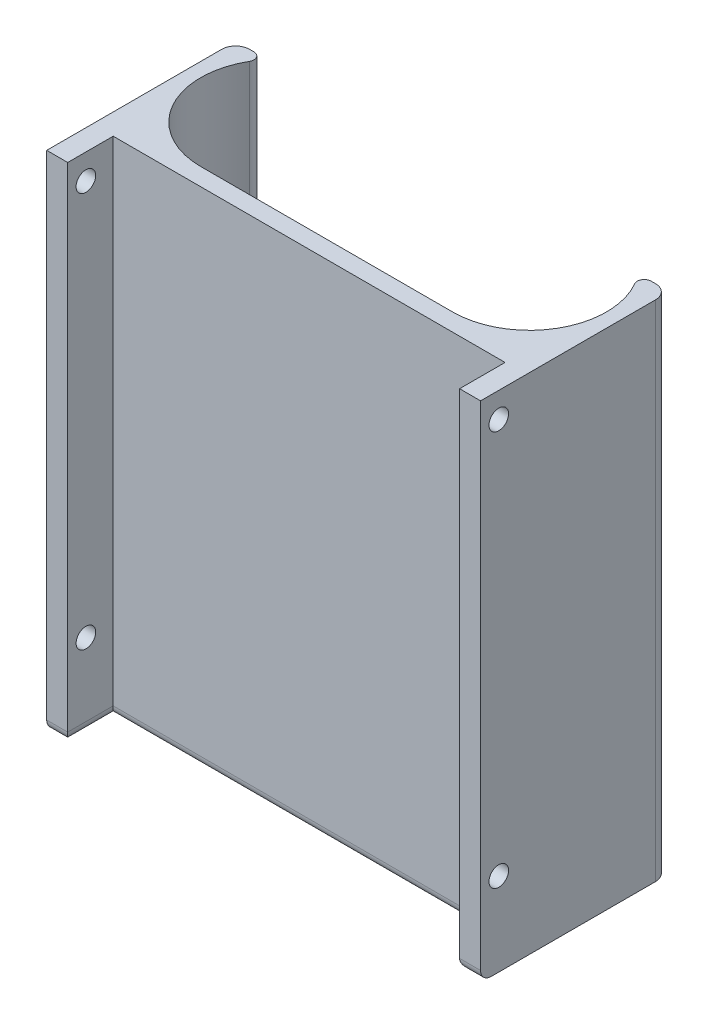
SolidWorks part; units mm, degrees
ref_plane "Front Plane" through (0, 0, 0) normal (0, 0, 1) x (1, 0, 0)
ref_plane "Top Plane" through (0, 0, 0) normal (0, 1, 0) x (1, 0, 0)
ref_plane "Right Plane" through (0, 0, 0) normal (1, 0, 0) x (0, 0, -1)
sketch "Sketch1" plane through (0, 0, 0) normal (0, 1, 0) x (1, 0, 0)
  line L0 (-31, 0) -> (31, 0) construction
  line L1 (-31, 13.5) -> (-31, -13.5)
  line L2 (0, 0) -> (0, 18.0266) construction
  line L3 (31, 13.5) -> (31, -13.5)
  line L4 (-28, 13.5) -> (-28, -7) construction
  line L5 (28, 13.5) -> (28, -7) construction
  line L6 (-28, -7) -> (28, -7)
  line L7 (28, 13.5) -> (-28, 13.5)
  line L8 (-31, 13.5) -> (-28, 13.5)
  line L10 (31, 13.5) -> (28, 13.5)
  line L12 (28, -7) -> (28, -13.5)
  line L13 (28, -13.5) -> (31, -13.5)
  line L14 (-28, -7) -> (-28, -13.5)
  line L15 (-28, -13.5) -> (-31, -13.5)
  dimension "D1" = 62
  dimension "D2" = 27
  dimension "D3" = 20.5
  dimension "D4" = 3
extrude "Boss-Extrude1" add sketch "Sketch1" along normal blind 72
sketch "Sketch2" plane through (0, 72, 0) normal (0, 1, 0) x (1, 0, 0)
  line L0 (18, 17.5) -> (-18, 17.5001)
  line L1 (-18, -4.5001) -> (18, -4.5)
  line L2 (18, 15.5) -> (-18, 15.5001)
  line L3 (-18, -2.5001) -> (18, -2.5)
  line L4 (18, 15.5) -> (-18, 15.5001) construction
  line L5 (-18, -2.5001) -> (18, -2.5) construction
  arc A0 (-18, 17.5001) -> (-18, -4.5001) centre (-18, 6.5) ccw
  arc A1 (18, -4.5) -> (18, 17.5) centre (18, 6.5) ccw
  arc A2 (18, -2.5) -> (18, 15.5) centre (18, 6.5) ccw
  arc A3 (-18, 15.5001) -> (-18, -2.5001) centre (-18, 6.5) ccw
  arc A4 (18, -2.5) -> (18, 15.5) centre (18, 6.5) ccw construction
  arc A5 (-18, 15.5001) -> (-18, -2.5001) centre (-18, 6.5) ccw construction
  dimension "D1" = 0
  dimension "D2" = 2
extrude "Cut-Extrude1" cut sketch "Sketch2" against normal blind 65
fillet "Fillet3" radius 2 2 edges at (-31, 36, -13.5) (31, 36, -13.5)
fillet "Fillet4" radius 1.5 5 edges at (29.5, 0, 13.5) (28, 0, 10.25) (-29.5, 0, 13.5) (-28, 0, 10.25) (0, 0, 7)
sketch "Sketch4" plane through (0, 72, 0) normal (0, 1, 0) x (1, 0, 0)
  line L1 (-31, -13.5) -> (-28, -13.5)
  line L2 (-31, -13.5) -> (-31, -7)
  line L3 (-31, -7) -> (-28, -7)
  line L4 (-28, -13.5) -> (-28, -7)
  line L5 (31, -13.5) -> (28, -13.5)
  line L6 (31, -13.5) -> (31, -7)
  line L7 (31, -7) -> (28, -7)
  line L8 (28, -13.5) -> (28, -7)
sketch "Sketch5" plane through (-31, 0, 0) normal (-1, 0, 0) x (0, 0, 1)
  arc A0 (12.15, 11.9) -> (9.65, 11.9) centre (10.9, 11.9) ccw construction
  arc A1 (9.65, 11.9) -> (12.15, 11.9) centre (10.9, 11.9) ccw construction
  arc A2 (12.15, 68.4) -> (9.65, 68.4) centre (10.9, 68.4) ccw construction
  arc A3 (9.65, 68.4) -> (12.15, 68.4) centre (10.9, 68.4) ccw construction
  arc A4 (12.15, 11.9) -> (9.65, 11.9) centre (10.9, 11.9) ccw construction
  arc A5 (9.65, 11.9) -> (12.15, 11.9) centre (10.9, 11.9) ccw construction
  arc A6 (12.15, 68.4) -> (9.65, 68.4) centre (10.9, 68.4) ccw construction
  arc A7 (9.65, 68.4) -> (12.15, 68.4) centre (10.9, 68.4) ccw construction
  circle A8 centre (10.9, 68.4) radius 1.4
  circle A9 centre (10.9, 11.9) radius 1.4
  dimension "D1" = 2.8
  dimension "D2" = 2.8
extrude "Cut-Extrude2" cut sketch "Sketch5" against normal through all
sketch "Sketch6" plane through (0, 0, 0) normal (0, 1, 0) x (1, 0, 0)
  line L0 (26.4853, 13.5) -> (-26.4854, 13.5) construction
  line L1 (-12.0001, 21.5) -> (11.9999, 21.5)
  line L2 (-12.0001, 21.5) -> (-12.0001, 13.5)
  line L3 (-12.0001, 13.5) -> (11.9999, 13.5)
  line L4 (11.9999, 21.5) -> (11.9999, 13.5)
  point P4 (-0.0001, 13.5)
  point P5 (-0.0001, 13.5)
  dimension "D1" = 24
  dimension "D2" = 8
extrude "Boss-Extrude3" add sketch "Sketch6" along normal up to surface (7 mm away) up to face at (0, 7, -3.1548)
fillet "Fillet5" radius 2 4 edges at (-12.0001, 3.5, -21.5) (-12.0001, 3.5, -13.5) (11.9999, 3.5, -13.5) (11.9999, 3.5, -21.5)
sketch "Sketch7" plane through (0, 7, 0) normal (0, 1, 0) x (1, 0, 0)
  line L0 (-12.0001, 19.5) -> (-12.0001, 15.5) construction
  line L1 (9.9999, 21.5) -> (-10.0001, 21.5) construction
  line L2 (11.9999, 15.5) -> (11.9999, 19.5) construction
  circle A0 centre (-8.0001, 17.5) radius 1.6
  circle A1 centre (7.9999, 17.5) radius 1.6
  point P0 (-8.0001, 17.5)
  point P5 (7.9999, 17.5)
  dimension "D5" = 3.2
  dimension "D6" = 3.2
  dimension "D1" = 4
  dimension "D2" = 4
  dimension "D3" = 4
  dimension "D4" = 4
extrude "Cut-Extrude3" cut sketch "Sketch7" against normal up to surface (7 mm away) up to face at (0, 0, -7.3238)
fillet "Fillet6" radius 1 2 edges at (26.4853, 39.5, -13.5) (-26.4854, 39.5, -13.5)
